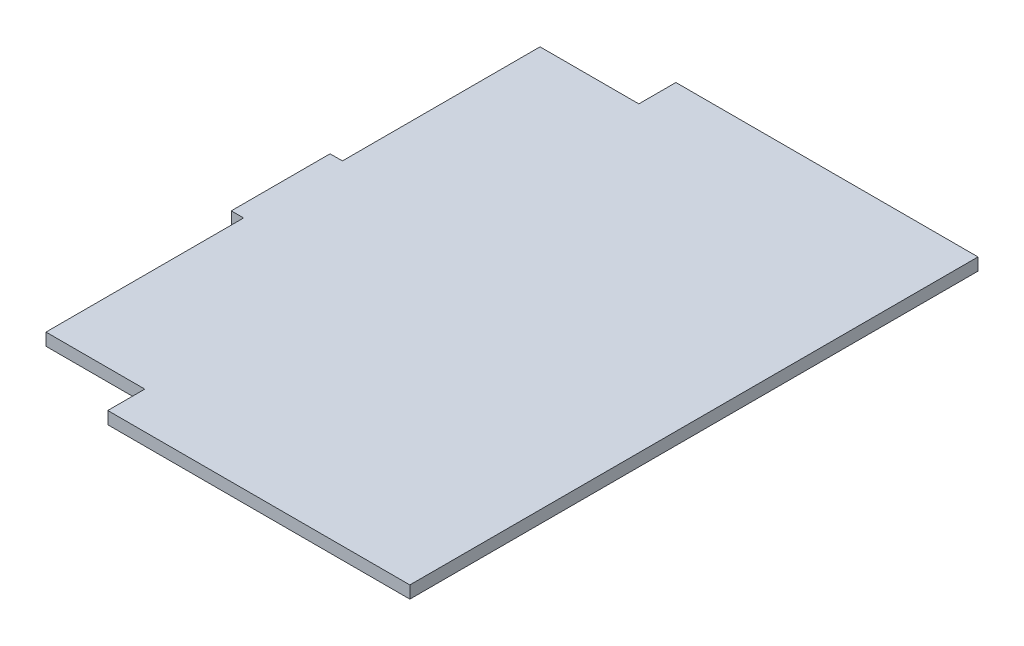
SolidWorks part; units mm, degrees
material "Acrylic (Medium-high impact)"
ref_plane "Front Plane" through (0, 0, 0) normal (0, 0, 1) x (1, 0, 0)
ref_plane "Top Plane" through (0, 0, 0) normal (0, 1, 0) x (1, 0, 0)
ref_plane "Right Plane" through (0, 0, 0) normal (1, 0, 0) x (0, 0, -1)
sketch "Sketch1" plane through (0, 0, 0) normal (0, 1, 0) x (1, 0, 0)
  line L0 (-66.1363, 66.4972) -> (66.1363, 66.4972) construction
  line L1 (66.1363, -73.025) -> (-66.1363, -73.025)
  line L2 (66.1363, -73.025) -> (66.1363, 73.025)
  line L3 (66.1363, 73.025) -> (-66.1363, 73.025)
  line L4 (-66.1363, -73.025) -> (-66.1363, 73.025)
  line L5 (66.1363, -73.025) -> (-66.1363, 73.025) construction
  line L6 (66.1363, 73.025) -> (-66.1363, -73.025) construction
  line L7 (-66.1363, -66.4972) -> (66.1363, -66.4972) construction
  line L8 (-66.1363, 66.4972) -> (-66.1363, -66.4972) construction
  line L9 (66.1363, 66.4972) -> (66.1363, -66.4972) construction
  line L19 (-66.1363, -12.7) -> (-69.3113, -12.7)
  line L20 (-66.1363, -73.025) -> (-40.7363, -73.025)
  line L21 (-66.1363, -73.025) -> (-66.1363, -63.5)
  line L22 (-66.1363, -63.5) -> (-40.7363, -63.5)
  line L23 (-40.7363, -73.025) -> (-40.7363, -63.5)
  line L24 (-66.1363, 73.025) -> (-40.7363, 73.025)
  line L25 (-66.1363, 73.025) -> (-66.1363, 63.5)
  line L26 (-66.1363, 63.5) -> (-40.7363, 63.5)
  line L27 (-40.7363, 73.025) -> (-40.7363, 63.5)
  line L28 (-66.1363, -12.7) -> (-66.1363, 12.7)
  line L29 (-66.1363, 12.7) -> (-69.3113, 12.7)
  line L30 (-69.3113, -12.7) -> (-69.3113, 12.7)
  line L31 (66.1363, 73.025) -> (59.7863, 73.025)
  line L32 (66.1363, 73.025) -> (66.1363, 63.5)
  line L33 (66.1363, 63.5) -> (59.7863, 63.5)
  line L34 (59.7863, 73.025) -> (59.7863, 63.5)
  line L35 (66.1363, -73.025) -> (59.7863, -73.025)
  line L36 (66.1363, -73.025) -> (66.1363, -63.5)
  line L37 (66.1363, -63.5) -> (59.7863, -63.5)
  line L38 (59.7863, -73.025) -> (59.7863, -63.5)
  point P0 (0, 0)
  point P10 (66.1363, 0)
  point P11 (66.1363, 0)
  point P16 (-69.3113, 0)
  dimension "D1" = 132.2725
  dimension "D2" = 146.05
  dimension "D3" = 132.9944
  dimension "D4" = 127
  dimension "D5" = 25.4
  dimension "D6" = 25.4
  dimension "D8" = 6.35
  dimension "D7" = 3.175
extrude "Boss-Extrude1" add sketch "Sketch1" along normal blind 3.175 contours L3 L27 L26 L4 L22 L23 L1 L2 | L30 L19 L4 L29
sketch "Sketch2" plane through (0, 0, 0) normal (0, -1, 0) x (1, 0, 0)
  line L0 (59.7863, -73.025) -> (-40.7363, -73.025) construction
  line L1 (36.9263, -73.025) -> (66.1363, -73.025)
  line L2 (36.9263, -73.025) -> (36.9263, 73.025)
  line L3 (36.9263, 73.025) -> (66.1363, 73.025)
  line L4 (66.1363, -73.025) -> (66.1363, 73.025)
  line L5 (59.7863, 73.025) -> (-40.7363, 73.025) construction
  line L6 (66.1363, 63.5) -> (66.1363, -63.5) construction
  line L7 (59.7863, -73.025) -> (59.7863, -63.5) construction
  dimension "D1" = 22.86
extrude "Cut-Extrude1" cut sketch "Sketch2" against normal through all
equation "\"WallThickness\"=0.125"
equation "\"D1@Boss-Extrude1\"=\"WallThickness\""
equation "\"D7@Sketch1\"=\"WallThickness\""
